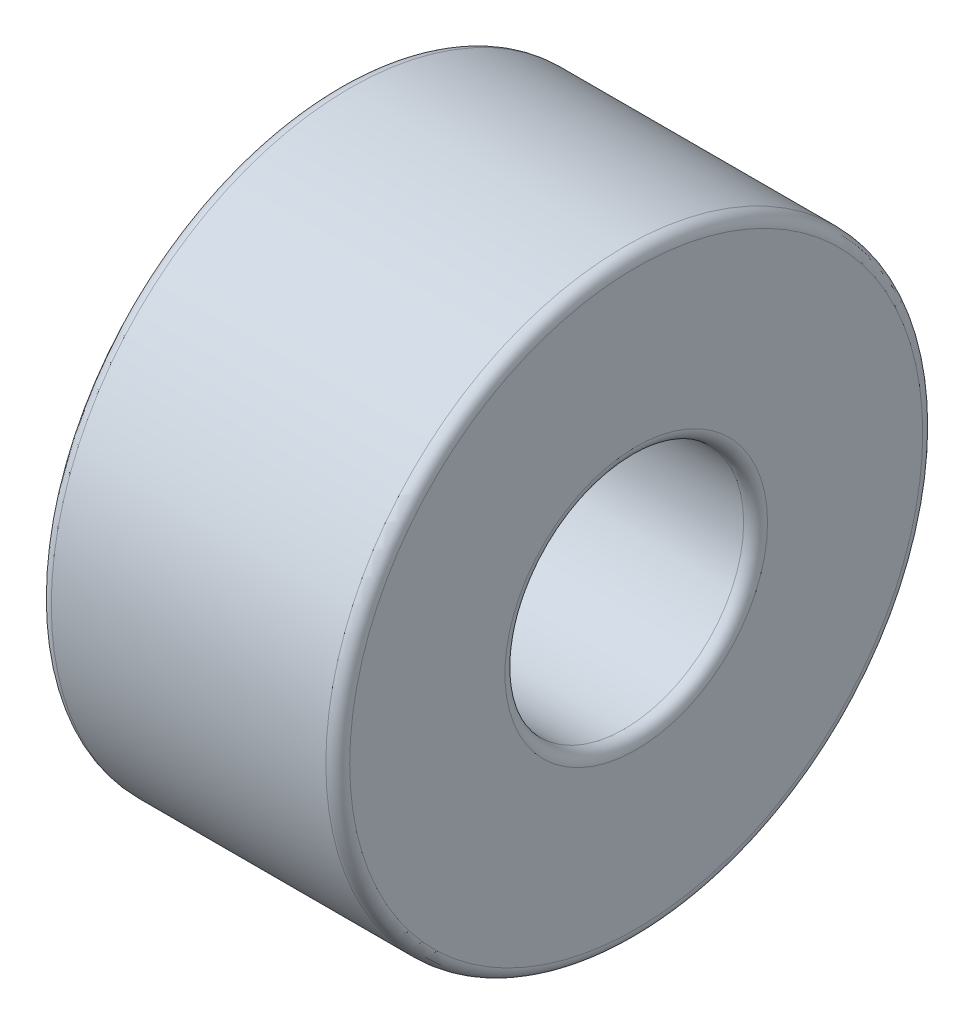
SolidWorks part; units mm, degrees
ref_plane "Front Plane" through (0, 0, 0) normal (0, 0, 1) x (1, 0, 0)
ref_plane "Top Plane" through (0, 0, 0) normal (0, 1, 0) x (1, 0, 0)
ref_plane "Right Plane" through (0, 0, 0) normal (1, 0, 0) x (0, 0, -1)
sketch "Sketch1" plane through (0, 0, 0) normal (1, 0, 0) x (0, 0, -1)
  circle A0 centre (0, 0) radius 2.5
  circle A1 centre (0, 0) radius 1
  dimension "D1" = 2
  dimension "D2" = 5
extrude "Boss-Extrude1" add sketch "Sketch1" along normal blind 2.5
fillet "Fillet1" radius 0.1 1 edges at (2.5, 0, -2.5)
fillet "Fillet2" radius 0.1 1 edges at (2.5, 0, -1)
fillet "Fillet3" radius 0.1 1 edges at (0, 0, -2.5)
fillet "Fillet4" radius 0.1 1 edges at (0, 0, -1)
